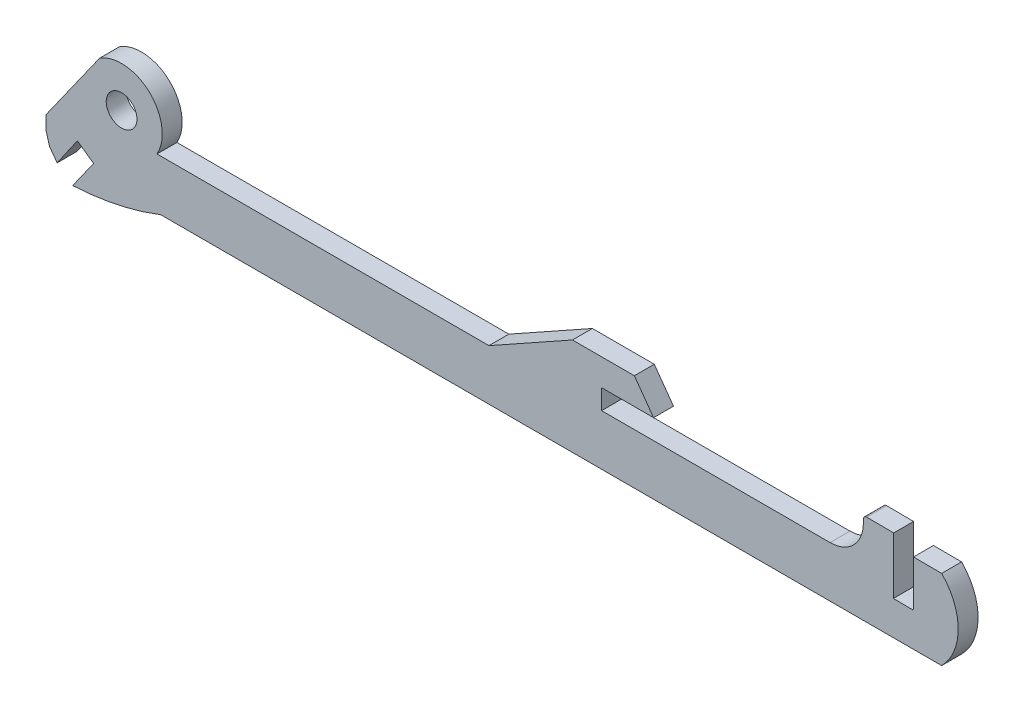
SolidWorks part; units mm, degrees
ref_plane "Front" through (0, 0, 0) normal (0, 0, 1) x (1, 0, 0)
ref_plane "Top" through (0, 0, 0) normal (0, 1, 0) x (1, 0, 0)
ref_plane "Right" through (0, 0, 0) normal (1, 0, 0) x (0, 0, -1)
sketch "Sketch1" plane through (0, 0, 0) normal (0, 0, 1) x (1, 0, 0)
  line L0 (1237.9121, -106.9654) -> (1245.9875, -95.5606)
  line L1 (1254.6344, -103.7344) -> (1304.6537, -103.7344)
  line L4 (1304.6537, -103.7344) -> (1317.2273, -96.7069)
  line L5 (1321.6205, -100.7344) -> (1321.6205, -103.7344)
  line L6 (1372.8559, -111.3832) -> (1255.1796, -111.3832)
  line L7 (1368.6201, -99.3233) -> (1368.5762, -106.2802)
  line L8 (1365.6304, -97.6839) -> (1365.5762, -106.2613)
  line L10 (1321.6205, -103.7344) -> (1356.0492, -103.7344)
  line L13 (1242.6367, -108.0137) -> (1239.5917, -112.4159)
  line L14 (1237.9238, -109.0557) -> (1237.9121, -106.9654)
  line L15 (1238.4603, -110.8843) -> (1237.9238, -109.0557)
  line L16 (1239.5917, -112.4159) -> (1238.4603, -110.8843)
  line L18 (1245.0861, -109.7459) -> (1242.6367, -108.0137)
  line L19 (1241.9361, -114.2003) -> (1245.0861, -109.7459)
  line L129 (1361.0625, -98.4777) -> (1361.0625, -98.1583)
  line L131 (1365.5762, -106.2613) -> (1368.5762, -106.2802)
  line L134 (1329.4524, -100.7344) -> (1321.6205, -100.7344)
  line L135 (1317.2273, -96.7069) -> (1326.5608, -96.7069)
  line L415 (1326.5608, -96.7069) -> (1329.4524, -100.7344)
  line L416 (1368.6201, -99.3233) -> (1372.8564, -99.35)
  line L417 (1361.5657, -97.6583) -> (1365.6304, -97.6839)
  line L420 (1361.0456, -98.924) -> (1361.0625, -98.4777)
  arc A0 (1372.8564, -99.35) -> (1372.8559, -111.3832) centre (1366.8395, -105.3664) cw
  arc A1 (1356.0492, -103.7344) -> (1361.0456, -98.924) centre (1356.0492, -98.7344) ccw
  arc A2 (1361.0625, -98.1583) -> (1361.5657, -97.6583) centre (1361.5625, -98.1583) cw
  arc A3 (1255.1796, -111.3832) -> (1241.9361, -114.2003) centre (1240.1244, -73.1446) cw
  arc A4 (1245.9875, -95.5606) -> (1254.6344, -103.7344) centre (1249.2991, -100.7178) cw
  circle A5 centre (1249.2991, -100.7178) radius 2.3147
  dimension "D4" = 5
  dimension "D5" = 0.5
  dimension "D1" = 90
  dimension "D2" = 90
  dimension "D3" = 3
  dimension "D6" = 3
  dimension "D7" = 90
  dimension "D8" = 90
  dimension "D9" = 3
extrude "Base-Extrude" add sketch "Sketch1" along normal blind 3
